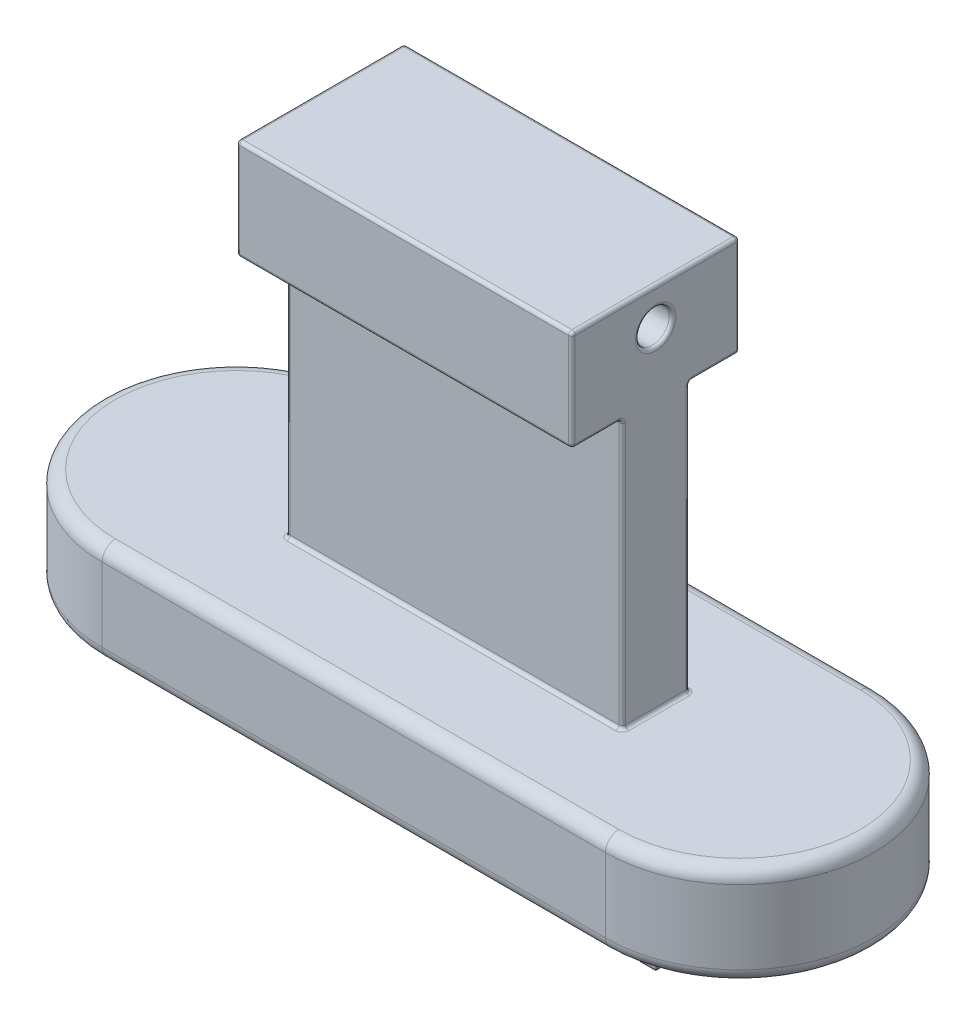
SolidWorks part; units mm, degrees
material "PE High Density"
ref_plane "Front Plane" through (0, 0, 0) normal (0, 0, 1) x (1, 0, 0)
ref_plane "Top Plane" through (0, 0, 0) normal (0, 1, 0) x (1, 0, 0)
ref_plane "Right Plane" through (0, 0, 0) normal (1, 0, 0) x (0, 0, -1)
sketch "Sketch1" plane through (0, 0, 0) normal (0, 1, 0) x (1, 0, 0)
  line L3 (-7.5, 1.5) -> (7.5, 1.5)
  line L4 (-7.5, -6.5) -> (7.5, -6.5)
  arc A0 (-7.5, 1.5) -> (-7.5, -6.5) centre (-7.5, -2.5) ccw
  arc A1 (7.5, 1.5) -> (7.5, -6.5) centre (7.5, -2.5) cw
  point P4 (0, 0)
  point P8 (-7.5, 0)
  point P11 (0, 0)
  point P15 (0, -6.5)
  point P16 (0, 1.5)
  dimension "D2" = 8
extrude "Boss-Extrude1" add sketch "Sketch1" along normal blind 3
fillet "Fillet1" radius 0.4 8 edges at (-11.5, 3, 2.5) (-11.5, 0, 2.5) (0, 0, -1.5) (0, 3, -1.5) (11.5, 3, 2.5) (11.5, 0, 2.5) (0, 3, 6.5) (0, 0, 6.5)
ref_plane "Plane1" through (0, 0, 0) normal (0, -1, 0) x (-1, 0, 0)
sketch "Sketch3" plane through (0, 0, 0) normal (0, -1, 0) x (-1, 0, 0)
  line L1 (0.25, 0.75) -> (-0.25, 0.75)
  line L2 (0.25, 0.75) -> (0.25, -0.75)
  line L4 (-0.25, -0.75) -> (-0.25, 0.75)
  line L37 (0.25, -0.75) -> (0.25, -5.75)
  line L38 (0.25, -5.75) -> (-0.25, -5.75)
  line L39 (-0.25, -5.75) -> (-0.25, -0.75)
  line L40 (2.25, 0.75) -> (1.75, 0.75)
  line L41 (1.75, -0.75) -> (1.75, 0.75)
  line L42 (2.25, 0.75) -> (2.25, -0.75)
  line L43 (2.25, -0.75) -> (2.25, -5.75)
  line L44 (1.75, -5.75) -> (1.75, -0.75)
  line L45 (2.25, -5.75) -> (1.75, -5.75)
  line L46 (4.25, 0.75) -> (3.75, 0.75)
  line L47 (3.75, -0.75) -> (3.75, 0.75)
  line L48 (4.25, 0.75) -> (4.25, -0.75)
  line L49 (4.25, -0.75) -> (4.25, -5.75)
  line L50 (3.75, -5.75) -> (3.75, -0.75)
  line L51 (4.25, -5.75) -> (3.75, -5.75)
  line L52 (6.25, 0.75) -> (5.75, 0.75)
  line L53 (5.75, -0.75) -> (5.75, 0.75)
  line L54 (6.25, 0.75) -> (6.25, -0.75)
  line L55 (6.25, -0.75) -> (6.25, -5.75)
  line L56 (5.75, -5.75) -> (5.75, -0.75)
  line L57 (6.25, -5.75) -> (5.75, -5.75)
  line L58 (8.25, 0.75) -> (7.75, 0.75)
  line L59 (7.75, -0.75) -> (7.75, 0.75)
  line L60 (8.25, 0.75) -> (8.25, -0.75)
  line L61 (8.25, -0.75) -> (8.25, -5.75)
  line L62 (7.75, -5.75) -> (7.75, -0.75)
  line L63 (8.25, -5.75) -> (7.75, -5.75)
  line L64 (-1.75, 0.75) -> (-2.25, 0.75)
  line L65 (-2.25, -0.75) -> (-2.25, 0.75)
  line L66 (-1.75, 0.75) -> (-1.75, -0.75)
  line L67 (-1.75, -0.75) -> (-1.75, -5.75)
  line L68 (-2.25, -5.75) -> (-2.25, -0.75)
  line L69 (-1.75, -5.75) -> (-2.25, -5.75)
  line L70 (-3.75, 0.75) -> (-4.25, 0.75)
  line L71 (-4.25, -0.75) -> (-4.25, 0.75)
  line L72 (-3.75, 0.75) -> (-3.75, -0.75)
  line L73 (-3.75, -0.75) -> (-3.75, -5.75)
  line L74 (-4.25, -5.75) -> (-4.25, -0.75)
  line L75 (-3.75, -5.75) -> (-4.25, -5.75)
  line L76 (-5.75, 0.75) -> (-6.25, 0.75)
  line L77 (-6.25, -0.75) -> (-6.25, 0.75)
  line L78 (-5.75, 0.75) -> (-5.75, -0.75)
  line L79 (-5.75, -0.75) -> (-5.75, -5.75)
  line L80 (-6.25, -5.75) -> (-6.25, -0.75)
  line L81 (-5.75, -5.75) -> (-6.25, -5.75)
  line L82 (-7.75, 0.75) -> (-8.25, 0.75)
  line L83 (-8.25, -0.75) -> (-8.25, 0.75)
  line L84 (-7.75, 0.75) -> (-7.75, -0.75)
  line L85 (-7.75, -0.75) -> (-7.75, -5.75)
  line L86 (-8.25, -5.75) -> (-8.25, -0.75)
  line L87 (-7.75, -5.75) -> (-8.25, -5.75)
  point P6 (0, 0)
  point P9 (0, 0.75)
  dimension "D2" = 0.5
ref_plane "Plane2" through (0, 3, 0) normal (0, 1, 0) x (1, 0, 0)
sketch "Sketch4" plane through (0, 3, 0) normal (0, 1, 0) x (1, 0, 0)
  line L0 (-11.1, -2.5) -> (11.1, -2.5)
  line L8 (-5, -3.5) -> (5, -3.5)
  line L9 (-5, -3.5) -> (-5, -1.5)
  line L10 (-5, -1.5) -> (5, -1.5)
  line L11 (5, -3.5) -> (5, -1.5)
  line L12 (-5, -3.5) -> (5, -1.5) construction
  line L13 (-5, -1.5) -> (5, -3.5) construction
  arc A0 (-7.5, 1.1) -> (-7.5, -6.1) centre (-7.5, -2.5) ccw construction
  arc A1 (7.5, -6.1) -> (7.5, 1.1) centre (7.5, -2.5) ccw construction
  point P0 (0, 0)
  point P1 (0, 0)
  point P15 (0, -2.5)
  dimension "D3" = 2
  dimension "D4" = 10
extrude "Boss-Extrude5" add sketch "Sketch3" along normal blind 0.5
fillet "Fillet5" radius 0.1 36 edges at (-8, -0.5, -0.75) (-8.25, -0.5, 2.5) (-8, -0.5, 5.75) (-7.75, -0.5, 2.5) (-6, -0.5, -0.75) (-6.25, -0.5, 2.5) (-6, -0.5, 5.75) (-5.75, -0.5, 2.5) (-4, -0.5, -0.75) (-4.25, -0.5, 2.5) (-4, -0.5, 5.75) (-3.75, -0.5, 2.5) (-2, -0.5, -0.75) (-2.25, -0.5, 2.5) (-2, -0.5, 5.75) (-1.75, -0.5, 2.5) (0, -0.5, -0.75) (-0.25, -0.5, 2.5) (0, -0.5, 5.75) (0.25, -0.5, 2.5) (2, -0.5, -0.75) (1.75, -0.5, 2.5) (2, -0.5, 5.75) (2.25, -0.5, 2.5) (4, -0.5, -0.75) (3.75, -0.5, 2.5) (4, -0.5, 5.75) (4.25, -0.5, 2.5) (6, -0.5, -0.75) (5.75, -0.5, 2.5) (6, -0.5, 5.75) (6.25, -0.5, 2.5) (8, -0.5, -0.75) (7.75, -0.5, 2.5) (8, -0.5, 5.75) (8.25, -0.5, 2.5)
extrude "Boss-Extrude6" add sketch "Sketch4" along normal blind 8 contours L0 L11 L10 L9 | L8 L11 L0 L9
ref_plane "Plane4" through (0, 11, 0) normal (0, 1, 0) x (1, 0, 0)
sketch "Sketch6" plane through (0, 11, 0) normal (0, 1, 0) x (1, 0, 0)
  line L0 (0, -1.5) -> (0, -3.5)
  line L1 (-5, -1.5) -> (5, -1.5) construction
  line L2 (-5, -3.5) -> (5, -3.5) construction
  line L4 (-5, -5) -> (5, -5)
  line L5 (-5, -5) -> (-5, 0)
  line L6 (-5, 0) -> (5, 0)
  line L7 (5, -5) -> (5, 0)
  line L8 (-5, -5) -> (5, 0) construction
  line L9 (-5, 0) -> (5, -5) construction
  point P6 (0, -2.5)
  dimension "D1" = 10
  dimension "D2" = 5
extrude "Boss-Extrude7" add sketch "Sketch6" along normal blind 3
fillet "Fillet6" radius 0.1 24 edges at (5, 11, 0.75) (5, 3, 2.5) (5, 11, 4.25) (5, 12.5, 5) (0, 11, 5) (0, 11, 3.5) (5, 7, 3.5) (0, 3, 3.5) (5, 14, 2.5) (0, 14, 5) (5, 12.5, 0) (0, 14, 0) (0, 11, 0) (5, 7, 1.5) (0, 11, 1.5) (0, 3, 1.5) (-5, 7, 1.5) (-5, 11, 0.75) (-5, 12.5, 0) (-5, 14, 2.5) (-5, 12.5, 5) (-5, 11, 4.25) (-5, 7, 3.5) (-5, 3, 2.5)
ref_plane "Plane5" through (-5, 0, 0) normal (-1, 0, 0) x (0, 0, 1)
sketch "Sketch8" plane through (-5, 0, 0) normal (-1, 0, 0) x (0, 0, 1)
  line L0 (2.5, 13.9) -> (2.5, 12.9)
  line L1 (4.9, 13.9) -> (0.1, 13.9) construction
  circle A0 centre (2.5, 12.9) radius 0.5
  dimension "D1" = 1
extrude "Cut-Extrude1" cut sketch "Sketch8" against normal blind 50
fillet "Fillet7" radius 0.1 2 edges at (5, 12.9, 3) (-5, 12.9, 3)
